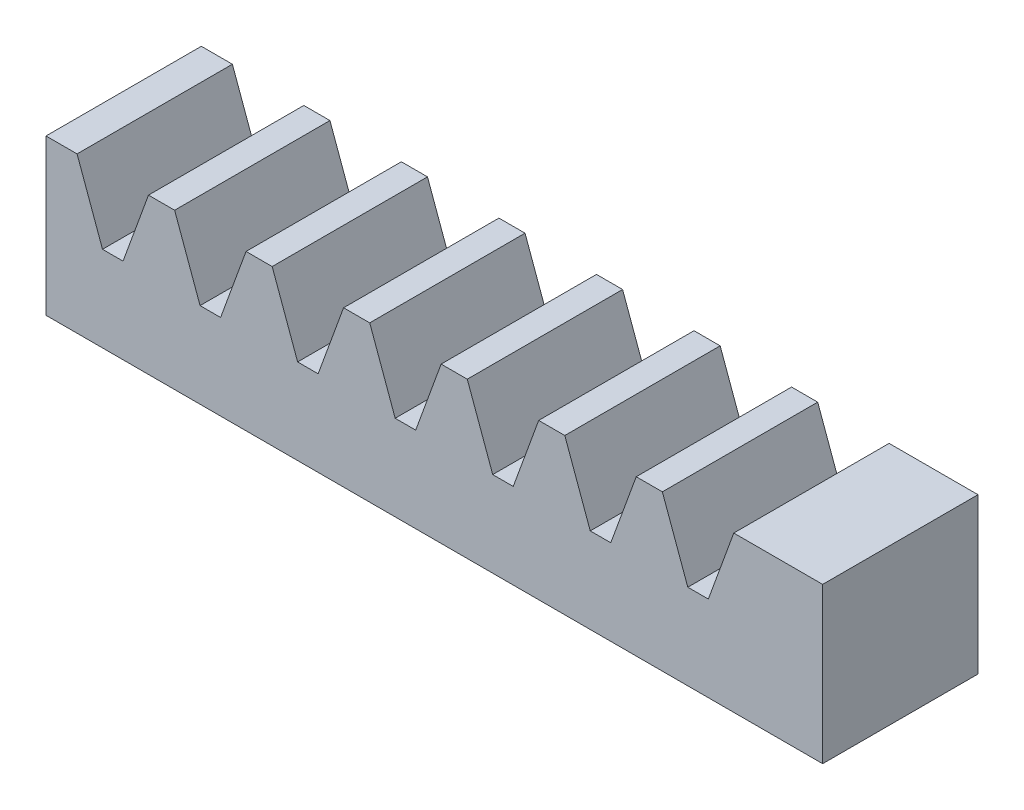
SolidWorks part; units mm, degrees
ref_plane "前视基准面" through (0, 0, 0) normal (0, 0, 1) x (1, 0, 0)
ref_plane "上视基准面" through (0, 0, 0) normal (0, 1, 0) x (1, 0, 0)
ref_plane "右视基准面" through (0, 0, 0) normal (1, 0, 0) x (0, 0, -1)
sketch "草图1" plane through (0, 0, 0) normal (0, 0, 1) x (1, 0, 0)
  line L1 (0, 0) -> (50, 0)
  line L2 (0, 0) -> (0, 10)
  line L3 (0, 10) -> (50, 10)
  line L4 (50, 0) -> (50, 10)
  dimension "H0" = 10
  dimension "L" = 50
extrude "凸台-拉伸1" add sketch "草图1" along normal blind 10
sketch "草图2" plane through (0, 0, 10) normal (0, 0, 1) x (1, 0, 0)
  line L0 (2, 10) -> (3.6379, 5.5)
  line L1 (50, 10) -> (0, 10) construction
  line L2 (3.6379, 5.5) -> (4.9596, 5.5)
  line L3 (4.9596, 5.5) -> (6.5975, 10)
  line L4 (6.5975, 10) -> (2, 10)
  line L5 (0, 8) -> (50, 8) construction
  line L6 (0, 10) -> (0, 0) construction
  line L7 (50, 0) -> (50, 10) construction
  line L9 (8.28, 10) -> (9.9179, 5.5) construction
  line L10 (9.9179, 5.5) -> (4.9596, 5.5) construction
  line L12 (8.28, 10) -> (6.5975, 10) construction
  point P12 (2.7279, 8)
  point P13 (5.8695, 8)
  point P14 (9.0079, 8)
  dimension "H" = 4.5
  dimension "H1" = 2
  dimension "A" = 2
  dimension "P" = 6.28
  dimension "E" = 3.1416
  dimension "D1" = 20
extrude "切除-拉伸1" cut sketch "草图2" against normal through all
pattern_linear "阵列(线性)1" count 7 spacing 6.28 along (1, 0, 0) of "切除-拉伸1"
equation "\"D3@阵列(线性)1\"= \"P@草图2\""
